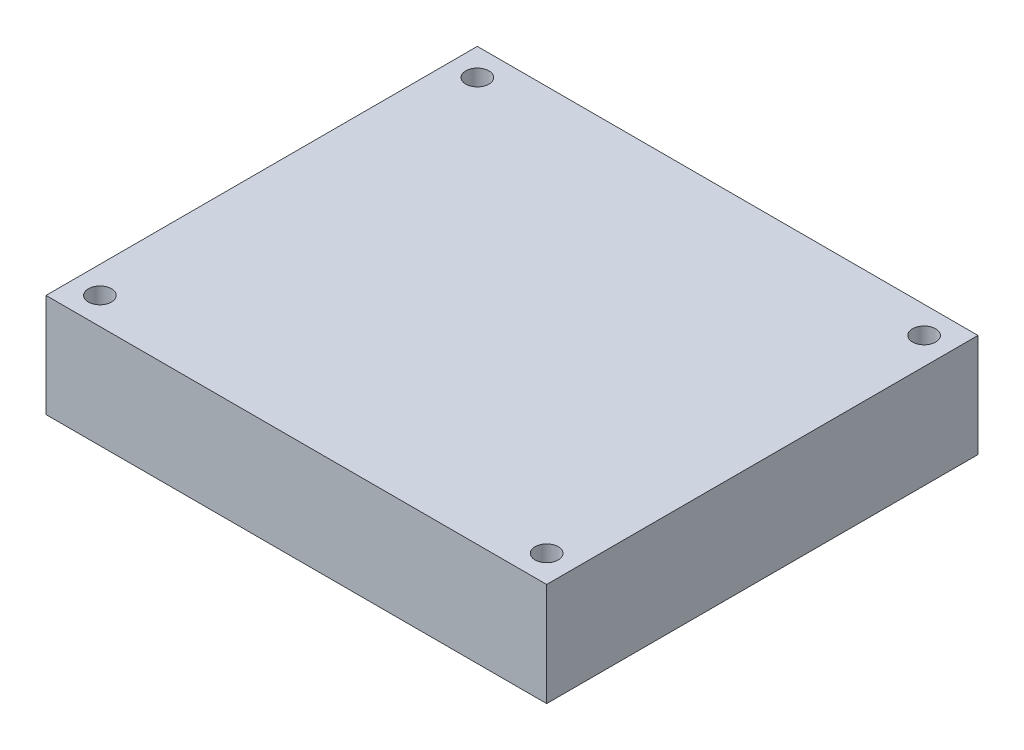
SolidWorks part; units mm, degrees
ref_plane "前视基准面" through (0, 0, 0) normal (0, 0, 1) x (1, 0, 0)
ref_plane "上视基准面" through (0, 0, 0) normal (0, 1, 0) x (1, 0, 0)
ref_plane "右视基准面" through (0, 0, 0) normal (1, 0, 0) x (0, 0, -1)
sketch "Sketch1" plane through (0, 0, 0) normal (0, 1, 0) x (1, 0, 0)
  line L1 (-32.5, 28) -> (32.5, 28)
  line L2 (-32.5, 28) -> (-32.5, -28)
  line L3 (-32.5, -28) -> (32.5, -28)
  line L4 (32.5, 28) -> (32.5, -28)
  line L5 (0, -28) -> (0, 28) construction
  line L6 (-32.5, 0) -> (32.5, 0) construction
  point P0 (0, 0)
  dimension "D1" = 65
  dimension "D2" = 56
extrude "Boss-Extrude1" add sketch "Sketch1" against normal blind 13.4
sketch "Sketch2" plane through (0, 0, 0) normal (0, 1, 0) x (1, 0, 0)
  line L1 (29, -24.5) -> (-29, -24.5) construction
  line L2 (29, -24.5) -> (29, 24.5) construction
  line L3 (29, 24.5) -> (-29, 24.5) construction
  line L4 (-29, -24.5) -> (-29, 24.5) construction
  line L5 (0, 24.5) -> (0, -24.5) construction
  line L6 (29, 0) -> (-29, 0) construction
  circle A0 centre (29, 24.5) radius 1.5
  circle A1 centre (29, -24.5) radius 1.5
  circle A2 centre (-29, -24.5) radius 1.5
  circle A3 centre (-29, 24.5) radius 1.5
  point P0 (0, 0)
  dimension "D3" = 3
  dimension "D1" = 49
  dimension "D2" = 58
extrude "Cut-Extrude1" cut sketch "Sketch2" against normal up to next
